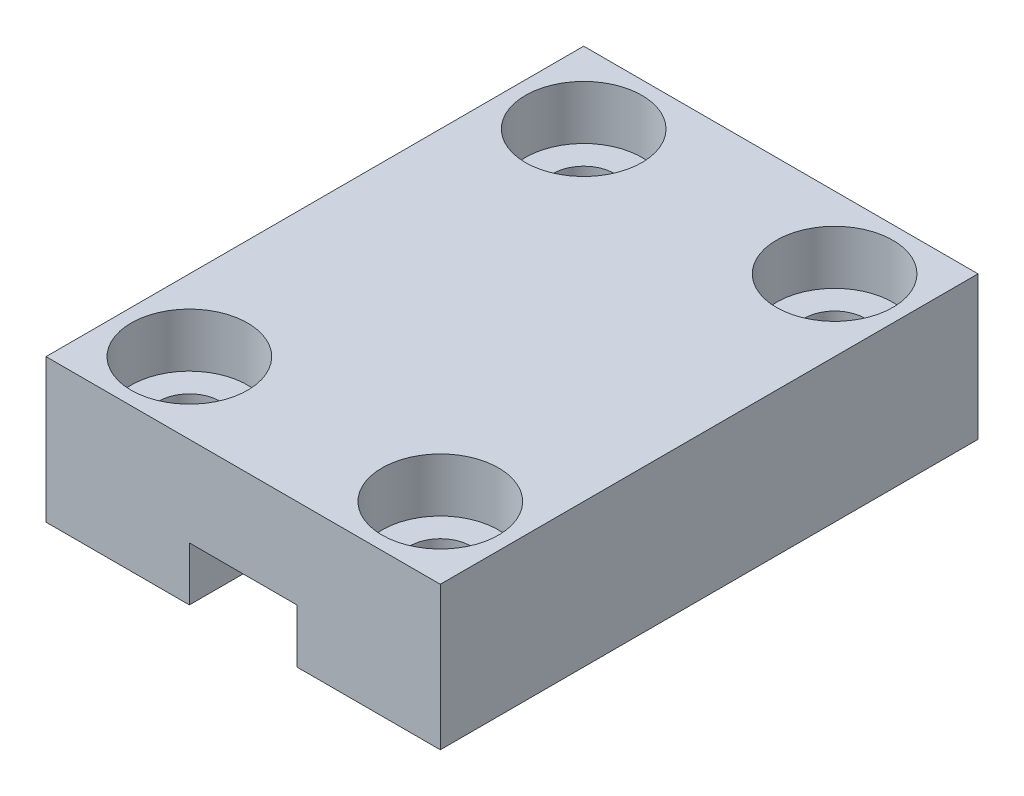
SolidWorks part; units mm, degrees
ref_plane "Спереди" through (0, 0, 0) normal (0, 0, 1) x (1, 0, 0)
ref_plane "Сверху" through (0, 0, 0) normal (0, 1, 0) x (1, 0, 0)
ref_plane "Справа" through (0, 0, 0) normal (1, 0, 0) x (0, 0, -1)
sketch "Эскиз1" plane through (0, 0, 0) normal (0, 0, 1) x (1, 0, 0)
  line L0 (-3, 0) -> (-11, 0)
  line L1 (-11, 0) -> (-11, 8)
  line L2 (-11, 8) -> (11, 8)
  line L3 (11, 8) -> (11, 0)
  line L4 (11, 0) -> (3, 0)
  line L5 (3, 0) -> (3, 3)
  line L6 (3, 3) -> (-3, 3)
  line L7 (-3, 3) -> (-3, 0)
  line L8 (0, 19.3958) -> (0, 0) construction
  point P11 (0, 8)
  point P12 (0, 3)
  dimension "D1" = 22
  dimension "D2" = 6
  dimension "D3" = 8
  dimension "D4" = 3
extrude "Бобышка-Вытянуть1" add sketch "Эскиз1" along normal blind 30
sketch "Эскиз2" plane through (0, 8, 0) normal (0, 1, 0) x (1, 0, 0)
  line L0 (-7, -26) -> (-7, -4) construction
  line L1 (-7, -4) -> (7, -4) construction
  line L2 (7, -4) -> (7, -26) construction
  line L3 (7, -26) -> (-7, -26) construction
  line L4 (-11, -30) -> (-11, 0) construction
  line L5 (11, -30) -> (11, 0) construction
  line L6 (11, -30) -> (-11, -30) construction
  line L7 (11, 0) -> (-11, 0) construction
  dimension "D1" = 4
  dimension "D2" = 4
  dimension "D3" = 4
  dimension "D4" = 4
hole_wizard "Цековка для винта с внутренним шестигранником M31" positions "Эскиз5" profile "Эскиз7" counterbore size "M3" standard "Ansi Metric" end condition through all
sketch "Эскиз5" plane through (0, 8, 0) normal (0, 1, 0) x (1, 0, 0)
  point P0 (-7, -4)
  point P3 (7, -4)
  point P6 (7, -26)
  point P9 (-7, -26)
sketch "Эскиз7" plane through (-7, 8, 4) normal (1, 0, 0) x (0, 0, 1)
  line L0 (0, 0) -> (0, 8)
  line L1 (0, 8) -> (1.7, 8)
  line L3 (1.7, 8) -> (1.7, 3)
  line L4 (1.7, 3) -> (3.25, 3)
  line L5 (3.25, 3) -> (3.25, 0)
  line L7 (3.25, 0) -> (0, 0)
  line L11 (0, -6.35) -> (0, 107.95) construction
  dimension "Диаметр сквозного отверстия" = 3.4
  dimension "Глубина сквозного отверстия" = 8
  dimension "Диаметр цековки" = 6.5
  dimension "Глубина цековки" = 3
